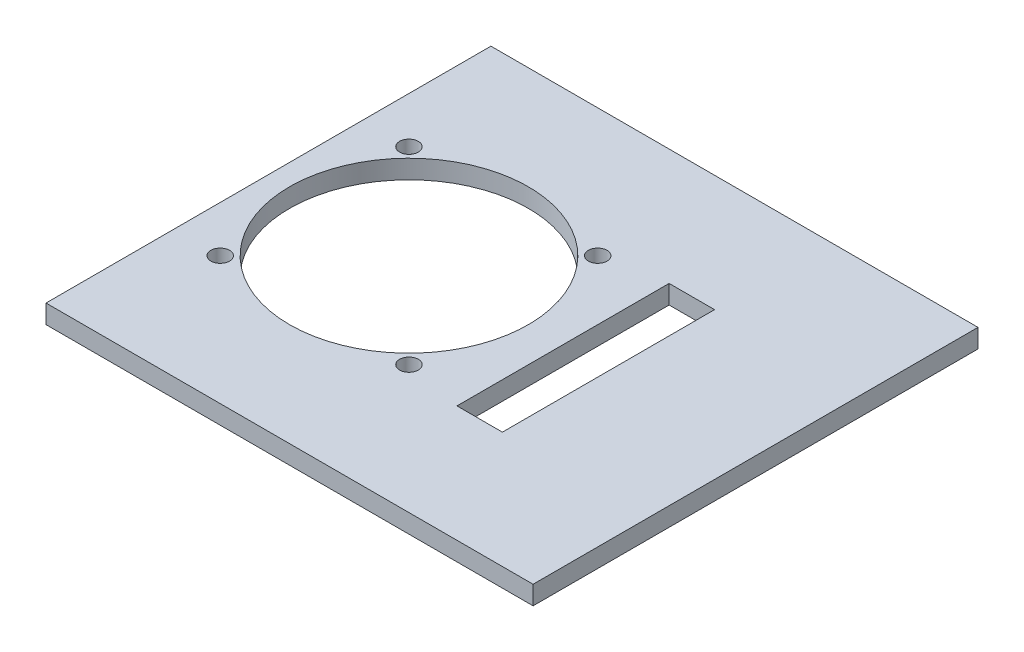
SolidWorks part; units mm, degrees
material "Beech"
ref_plane "Front Plane" through (0, 0, 0) normal (0, 0, 1) x (1, 0, 0)
ref_plane "Top Plane" through (0, 0, 0) normal (0, 1, 0) x (1, 0, 0)
ref_plane "Right Plane" through (0, 0, 0) normal (1, 0, 0) x (0, 0, -1)
sketch "Sketch1" plane through (0, 0, 0) normal (0, 1, 0) x (1, 0, 0)
  line L1 (-19.0795, 11.9639) -> (84.9205, 11.9639)
  line L2 (-19.0795, 11.9639) -> (-19.0795, -83.0361)
  line L3 (-19.0795, -83.0361) -> (84.9205, -83.0361)
  line L4 (84.9205, 11.9639) -> (84.9205, -83.0361)
  line L5 (43.8205, -12.8861) -> (53.5205, -12.8861)
  line L6 (43.8205, -12.8861) -> (43.8205, -58.1861)
  line L7 (43.8205, -58.1861) -> (53.5205, -58.1861)
  line L8 (53.5205, -12.8861) -> (53.5205, -58.1861)
  circle A0 centre (10.9205, -35.5361) radius 25.5
  circle A1 centre (-9.2295, -15.3861) radius 2
  circle A2 centre (-9.2295, -55.6861) radius 2
  circle A3 centre (31.0705, -55.6861) radius 2
  circle A4 centre (31.0705, -15.3861) radius 2
  dimension "D5" = 51
  dimension "D13" = 4
  dimension "D14" = 4
  dimension "D16" = 4
  dimension "D18" = 4
  dimension "D1" = 95
  dimension "D2" = 104
  dimension "D3" = 9.7
  dimension "D4" = 45.3
  dimension "D6" = 24.85
  dimension "D7" = 32.9
  dimension "D8" = 30
  dimension "D9" = 47.5
  dimension "D10" = 31.4
  dimension "D11" = 20.15
  dimension "D12" = 20.15
  dimension "D15" = 20.15
  dimension "D17" = 20.15
extrude "Boss-Extrude1" add sketch "Sketch1" along normal blind 4
